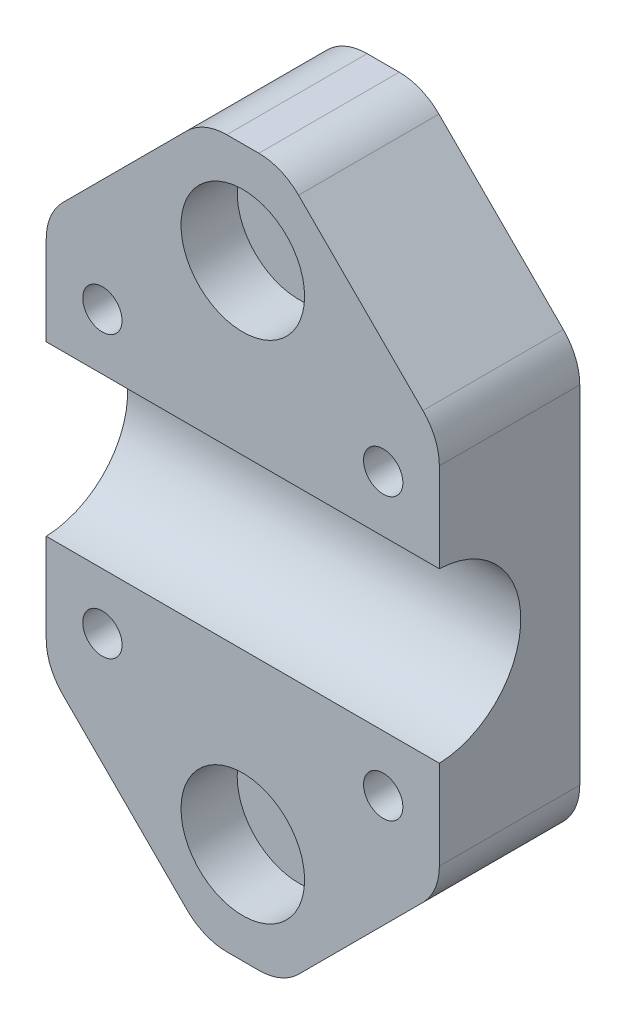
SolidWorks part; units mm, degrees
ref_plane "XY" through (0, 0, 0) normal (0, 0, 1) x (1, 0, 0)
ref_plane "XZ" through (0, 0, 0) normal (0, 1, 0) x (1, 0, 0)
ref_plane "YZ" through (0, 0, 0) normal (1, 0, 0) x (0, 0, -1)
sketch "Sketch1" plane through (0, 0, 0) normal (0, 0, 1) x (1, 0, 0)
  line L0 (-3.5, 31.5) -> (-17.5, 17.5)
  line L1 (17.5, 31.5) -> (3.5, 31.5) construction
  line L2 (17.5, 31.5) -> (17.5, 17.5) construction
  line L3 (17.5, -31.5) -> (3.5, -31.5) construction
  line L4 (-17.5, 31.5) -> (-17.5, 17.5) construction
  line L5 (17.5, 31.5) -> (-17.5, -31.5) construction
  line L6 (17.5, -31.5) -> (-17.5, 31.5) construction
  line L7 (0, 0) -> (0, 36.1303) construction
  line L8 (0, 0) -> (-42.5592, 0) construction
  line L9 (3.5, 31.5) -> (17.5, 17.5)
  line L10 (3.5, -31.5) -> (17.5, -17.5)
  line L11 (-3.5, -31.5) -> (-17.5, -17.5)
  line L12 (-17.5, 17.5) -> (-17.5, -17.5)
  line L13 (-17.5, -17.5) -> (-17.5, -31.5) construction
  line L14 (17.5, -17.5) -> (17.5, -31.5) construction
  line L15 (17.5, 17.5) -> (17.5, -17.5)
  line L16 (-3.5, 31.5) -> (-17.5, 31.5) construction
  line L17 (3.5, 31.5) -> (-3.5, 31.5)
  line L18 (-3.5, -31.5) -> (-17.5, -31.5) construction
  line L19 (3.5, -31.5) -> (-3.5, -31.5)
  point P0 (0, 0)
  dimension "D1" = 35
  dimension "D2" = 63
  dimension "D3" = 14
  dimension "D4" = 14
extrude "Boss-Extrude1" add sketch "Sketch1" along normal blind 12.5
sketch "Sketch2" plane through (17.5, 0, 0) normal (1, 0, 0) x (0, 0, -1)
  line L0 (-12.5, -17.5) -> (-12.5, 17.5) construction
  line L1 (-12.5, -7.4958) -> (-12.5, 7.4958)
  arc A0 (-12.5, -7.4958) -> (-12.5, 7.4958) centre (-12.75, 0) ccw
  dimension "D1" = 15
  dimension "D2" = 12.75
extrude "Cut-Extrude1" cut sketch "Sketch2" against normal up to next
sketch "Sketch3" plane through (0, 0, 0) normal (0, 0, -1) x (-1, 0, 0)
  line L0 (0, 0) -> (0, 20.4714) construction
  line L1 (0, 0) -> (-26.9924, 0) construction
  circle A0 centre (-12.5, 12.5) radius 3
  circle A1 centre (12.5, 12.5) radius 3
  circle A2 centre (12.5, -12.5) radius 3
  circle A3 centre (-12.5, -12.5) radius 3
  dimension "D1" = 6
  dimension "D2" = 12.5
  dimension "D3" = 12.5
extrude "Cut-Extrude2" cut sketch "Sketch3" against normal blind 3
sketch "Sketch4" plane through (0, 0, 12.5) normal (0, 0, 1) x (1, 0, 0)
  line L0 (-0.6363, 0) -> (39.3124, 0) construction
  circle A0 centre (0, 22.5) radius 5.5
  circle A1 centre (0, -22.5) radius 5.5
  dimension "D1" = 11
  dimension "D2" = 22.5
extrude "Cut-Extrude3" cut sketch "Sketch4" against normal blind 5
fillet "Fillet1" radius 5 8 edges at (-3.5, -31.5, 6.25) (3.5, -31.5, 6.25) (17.5, -17.5, 6.25) (17.5, 17.5, 6.25) (-17.5, -17.5, 6.25) (3.5, 31.5, 6.25) (-3.5, 31.5, 6.25) (-17.5, 17.5, 6.25)
sketch "Sketch5" plane through (0, 0, 12.5) normal (0, 0, 1) x (1, 0, 0)
  line L0 (0, 0) -> (0, 13.9425) construction
  line L1 (0, 0) -> (-26.6208, 0) construction
  circle A0 centre (-12.5, 12.5) radius 1.75
  circle A1 centre (12.5, 12.5) radius 1.75
  circle A2 centre (12.5, -12.5) radius 1.75
  circle A3 centre (-12.5, -12.5) radius 1.75
  point P8 (0, 0)
  dimension "D1" = 12.5
  dimension "D3" = 3.5
  dimension "D2" = 12.5
extrude "Cut-Extrude4" cut sketch "Sketch5" against normal blind 9.1
